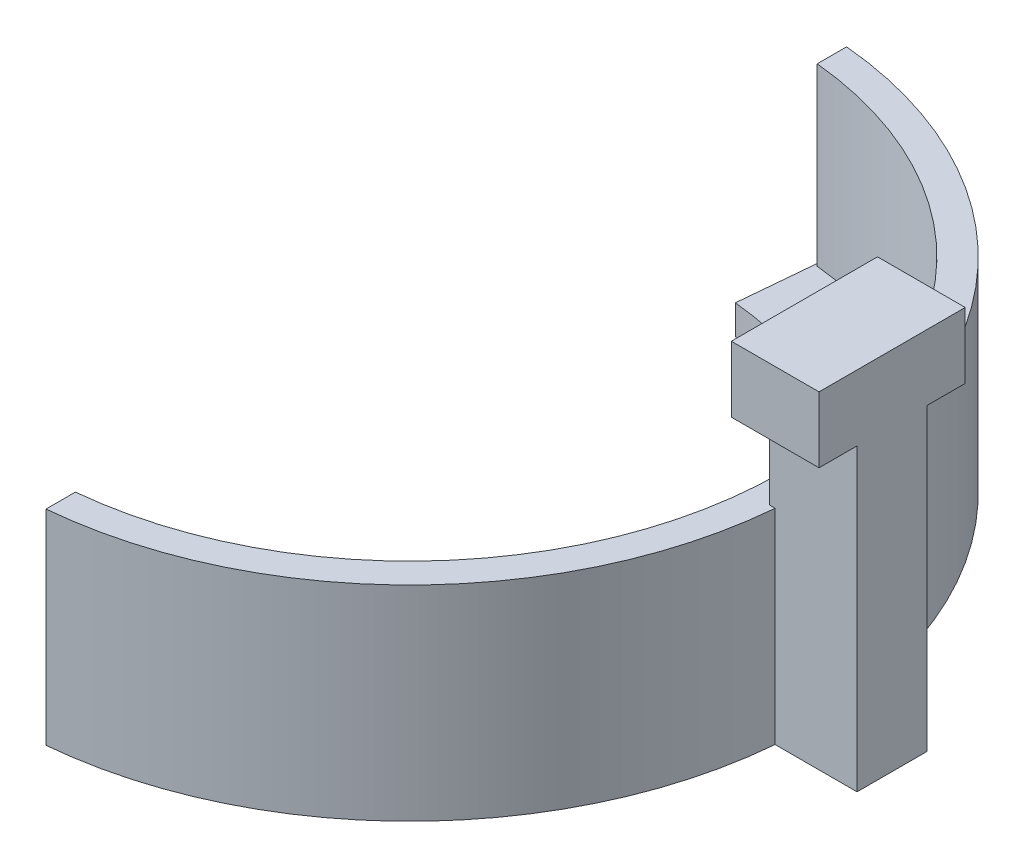
SolidWorks part; units mm, degrees
ref_plane "Front Plane" through (0, 0, 0) normal (0, 0, 1) x (1, 0, 0)
ref_plane "Top Plane" through (0, 0, 0) normal (0, 1, 0) x (1, 0, 0)
ref_plane "Right Plane" through (0, 0, 0) normal (1, 0, 0) x (0, 0, -1)
sketch "Sketch1" plane through (0, 0, 0) normal (0, 1, 0) x (1, 0, 0)
  line L4 (2.5, 27.3861) -> (2.5, 25.3772)
  line L6 (-2.5, 0) -> (2.5, 0) construction
  line L7 (2.5, -25.3772) -> (2.5, -27.3861)
  arc A2 (2.5, -27.3861) -> (2.5, 27.3861) centre (0, 0) ccw
  arc A5 (2.5, -25.3772) -> (2.5, 25.3772) centre (0, 0) ccw
  point P4 (24.3858, 7.4555)
  point P12 (26.2984, 8.0402)
extrude "Boss-Extrude3" add sketch "Sketch1" along normal blind 12
sketch "Sketch2" plane through (0, 0, 0) normal (0, 1, 0) x (1, 0, 0)
  line L0 (2.5, -25.3772) -> (2.5, -27.3861) construction
  line L1 (2.5, 27.3861) -> (1.8636, 20.4151)
  line L2 (2.5, -27.3861) -> (1.8636, -20.4151)
  arc A0 (2.5, 27.3861) -> (2.5, -27.3861) centre (0, 0) cw
  arc A1 (2.5, -27.3861) -> (2.5, 27.3861) centre (0, 0) ccw construction
  arc A2 (1.8636, 20.4151) -> (1.8636, -20.4151) centre (0, 0) cw
  dimension "D1" = 7
extrude "Boss-Extrude4" add sketch "Sketch2" against normal blind 2
sketch "Sketch3" plane through (0, -2, 0) normal (0, -1, 0) x (1, 0, 0)
  line L1 (27, -2.4) -> (33, -2.4)
  line L2 (27, -2.4) -> (27, 2.4)
  line L3 (27, 2.4) -> (33, 2.4)
  line L4 (33, -2.4) -> (33, 2.4)
  line L5 (30, 2.4) -> (30, -2.4) construction
  line L6 (27, 0) -> (33, 0) construction
  point P0 (30, 0)
  dimension "D1" = 30
  dimension "D2" = 4.8
  dimension "D3" = 6
extrude "Boss-Extrude5" add sketch "Sketch3" against normal blind 22
sketch "Sketch4" plane through (0, 20, 0) normal (0, 1, 0) x (1, 0, 0)
  line L0 (33, 2.4) -> (33, -2.4) construction
  line L1 (27, 5) -> (33, 5)
  line L2 (27, 5) -> (27, -5)
  line L3 (27, -5) -> (33, -5)
  line L4 (33, 5) -> (33, -5)
  line L5 (30, -5) -> (30, 5) construction
  line L6 (27, 0) -> (33, 0) construction
  point P0 (30, 0)
  dimension "D1" = 10
  dimension "D2" = 6
  dimension "D3" = 3
extrude "Boss-Extrude6" add sketch "Sketch4" along normal blind 3 and the other way blind 1.5
ref_plane "Plane1" through (0, 18.5, 0) normal (0, -1, 0) x (-1, 0, 0)
